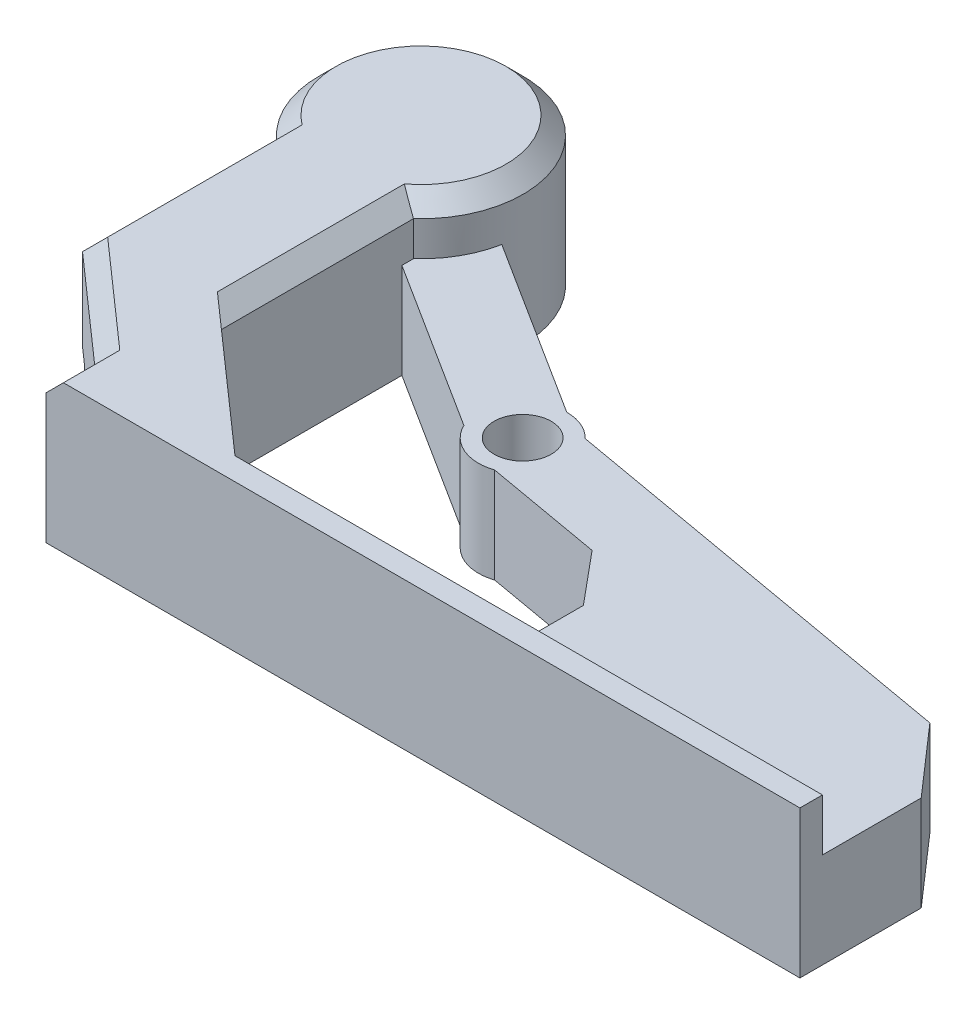
SolidWorks part; units mm, degrees
ref_plane "Front Plane" through (0, 0, 0) normal (0, 0, 1) x (1, 0, 0)
ref_plane "Top Plane" through (0, 0, 0) normal (0, 1, 0) x (1, 0, 0)
ref_plane "Right Plane" through (0, 0, 0) normal (1, 0, 0) x (0, 0, -1)
sketch "Sketch1" plane through (0, 0, 0) normal (0, 1, 0) x (1, 0, 0)
  line L0 (21.75, 0) -> (-21.75, 0)
  line L1 (-21.75, 0) -> (-21.75, 1.3)
  line L2 (-21.75, 1.3) -> (21.75, 1.3)
  line L3 (21.75, 1.3) -> (21.75, 0)
  line L4 (21.75, 0) -> (21.75, 7)
  line L5 (21.75, 7) -> (18.25, 11)
  line L6 (18.25, 11) -> (-7.25, 15.5)
  line L7 (-7.9973, 11.2654) -> (-0.119, 9.8751)
  line L8 (-7.25, 15.5) -> (-7.9973, 11.2654)
  line L9 (-0.119, 9.8751) -> (2.381, 6.8751)
  line L10 (2.381, 6.8751) -> (2.381, 1.3)
  line L11 (-8.9018, 11.6845) -> (-6.5982, 15.3155)
  line L12 (-6.5982, 15.3155) -> (-21.7974, 24.9583)
  line L13 (-21.7974, 24.9583) -> (-24.101, 21.3274)
  line L14 (-24.101, 21.3274) -> (-8.9018, 11.6845)
  line L15 (-7.75, 13.5) -> (-23.8, 23.6826) construction
  line L16 (-21.75, 0) -> (-21.75, 2.8)
  line L17 (-21.75, 2.8) -> (-27.75, 8.1)
  line L18 (-27.75, 8.1) -> (-27.75, 19.3)
  line L19 (-27.75, 19.3) -> (-19.85, 19.3)
  line L20 (-19.85, 19.3) -> (-19.85, 8.1)
  line L21 (-19.85, 8.1) -> (-12.1519, 1.3)
  circle A0 centre (-7.75, 13.5) radius 1.65
  circle A1 centre (-7.75, 13.5) radius 2.55
  circle A2 centre (-23.8, 23.6826) radius 5.9
  point P4 (0, 0)
  dimension "D15" = 3.3
  dimension "D16" = 5.1
  dimension "D25" = 11.8
  dimension "D1" = 1.3
  dimension "D2" = 43.5
  dimension "D3" = 0
  dimension "D4" = 7
  dimension "D5" = 4
  dimension "D6" = 3.5
  dimension "D7" = 29
  dimension "D8" = 15.5
  dimension "D9" = 4.3
  dimension "D10" = 8
  dimension "D11" = 3
  dimension "D12" = 2.5
  dimension "D13" = 29.5
  dimension "D14" = 13.5
  dimension "D17" = 4.3
  dimension "D18" = 18
  dimension "D19" = 2.8
  dimension "D20" = 6
  dimension "D21" = 5.3
  dimension "D22" = 11.2
  dimension "D23" = 7.9
  dimension "D24" = 11.2
extrude "Boss-Extrude1" add sketch "Sketch1" along normal blind 5.5
sketch "Sketch2" plane through (0, 5.5, 0) normal (0, 1, 0) x (1, 0, 0)
  circle A0 centre (-7.75, 13.5) radius 1.65
  dimension "D1" = 3.3
extrude "Cut-Extrude1" cut sketch "Sketch2" against normal blind 5.5
sketch "Sketch3" plane through (0, 5.5, 0) normal (0, 1, 0) x (1, 0, 0)
  line L0 (-19.85, 8.1) -> (-19.85, 19.3)
  line L1 (-27.75, 8.1) -> (-27.75, 19.3)
  line L2 (-27.75, 8.1) -> (-21.75, 2.8)
  line L3 (-21.75, 2.8) -> (-21.75, 0)
  line L4 (-21.75, 0) -> (21.75, 0)
  line L5 (21.75, 0) -> (21.75, 1.3)
  line L6 (21.75, 0) -> (21.75, 7) construction
  line L7 (21.75, 1.3) -> (-12.1519, 1.3)
  line L8 (-12.1519, 1.3) -> (-19.85, 8.1)
  circle A0 centre (-23.8, 23.6826) radius 5.9
  line M8 (2.381, 1.3) -> (-12.1519, 1.3)
  line M9 (-12.1519, 1.3) -> (-19.85, 8.1)
  line M10 (-19.85, 8.1) -> (-19.85, 18.6304)
  arc M14 (-18.0088, 22.5547) -> (-27.75, 19.3) centre (-23.8, 23.6826) ccw
  line M15 (-27.75, 19.3) -> (-27.75, 8.1)
  line M16 (-27.75, 8.1) -> (-21.75, 2.8)
  line M17 (-21.75, 2.8) -> (-21.75, 0)
  line M18 (-21.75, 0) -> (21.75, 0)
  line M19 (21.75, 0) -> (21.75, 7)
  dimension "D1" = 11.8
extrude "Boss-Extrude2" add sketch "Sketch3" along normal blind 3 contours A0 M14 | A0 L7 L0 M15 M16 M17 M18 M19 M8 M9 M10
sketch "Sketch4" plane through (0, 0, 0) normal (0, -1, 0) x (1, 0, 0)
  line L0 (-23.8, -29.5826) -> (-23.8, -7.3)
  line L1 (-23.8, -7.3) -> (-26.8443, -7.3)
  line L2 (-21.75, -2.8) -> (-27.75, -8.1) construction
  line L3 (-26.8443, -7.3) -> (-27.75, -8.1)
  line L4 (-27.75, -8.1) -> (-27.75, -19.3)
  arc A0 (-27.75, -19.3) -> (-18.0088, -22.5547) centre (-23.8, -23.6826) ccw construction
  circle A1 centre (-23.8, -23.6826) radius 5.9
  line M18 (-21.75, -2.8) -> (-27.75, -8.1)
  line M19 (-27.75, -8.1) -> (-27.75, -19.3)
  arc M20 (-27.75, -19.3) -> (-18.0088, -22.5547) centre (-23.8, -23.6826) ccw
  dimension "D2" = 11.8
  dimension "D1" = 0.8
extrude "Cut-Extrude2" cut sketch "Sketch4" against normal offset from surface (2.75 mm away) 5.75 contours L0 A1 M20 | A1 L0 L1 M18 M19
sketch "Sketch5" plane through (0, 0, 0) normal (0, -1, 0) x (1, 0, 0)
  line L0 (21.75, 0) -> (-21.75, 0) construction
  circle A0 centre (-23.8, -23.6826) radius 1.95
  circle A1 centre (-23.8, -13.8826) radius 1.35
  circle A2 centre (-20, -4.3826) radius 1.15
  circle A3 centre (15.0006, -5.5) radius 2
  dimension "D1" = 3.9
  dimension "D3" = 2.7
  dimension "D7" = 2.3
  dimension "D8" = 4
  dimension "D2" = 0
  dimension "D4" = 3.8
  dimension "D5" = 9.5
  dimension "D6" = 9.8
  dimension "D9" = 38.8006
  dimension "D10" = 5.5
extrude "Cut-Extrude3" cut sketch "Sketch5" against normal offset from surface (4.3 mm away) 1.2 up to face at (-1.7017, 5.5, -11.7406)
sketch "Sketch7" plane through (0, 4.3, 0) normal (0, -1, 0) x (1, 0, 0)
  circle A0 centre (-23.8, -13.8826) radius 1.35
  circle A1 centre (-23.8, -23.6826) radius 1.95
  dimension "D1" = 3.9
  dimension "D2" = 2.7
extrude "Cut-Extrude4" cut sketch "Sketch7" against normal offset from surface (3 mm away) 1.2 contours A1 | A0 up to face at (-11.928, 8.5, -7.8314)
chamfer "Chamfer1" distance 1 angle 45 5 edges at (-21.75, 8.5, -1.4) (-24.75, 8.5, -5.45) (-27.75, 8.5, -13.7) (-19.85, 8.5, -13.7) (-23.8, 8.5, -29.5826)
sketch "Sketch8" plane through (0, 0, 0) normal (0, -1, 0) x (1, 0, 0)
  line L0 (-23.8, -7.3) -> (-21.05, -7.3)
  line L1 (-21.05, -7.3) -> (-21.05, -19.8711)
  line L2 (-19.85, -18.6304) -> (-19.85, -8.1) construction
  line L3 (-23.8, -7.3) -> (-23.8, -18.9826)
  circle A0 centre (-23.8, -23.6826) radius 4.7
  arc A1 (-23.8, -29.5826) -> (-18.0088, -22.5547) centre (-23.8, -23.6826) ccw construction
  line M13 (-23.8, -15.2326) -> (-23.8, -21.7326)
  arc M14 (-23.8, -21.7326) -> (-23.8, -25.6326) centre (-23.8, -23.6826) cw
  line M15 (-23.8, -25.6326) -> (-23.8, -29.5826)
  line M26 (-23.8, -7.3) -> (-23.8, -12.5326)
  arc M27 (-23.8, -12.5326) -> (-23.8, -15.2326) centre (-23.8, -13.8826) cw
  dimension "D1" = 1.2
  dimension "D2" = 1.2
extrude "Cut-Extrude5" cut sketch "Sketch8" against normal up to surface (2.75 mm away) contours A0 L1 L0 M26 M27 M13 | A0 M15 M13 M14 up to face at (-25.7752, 2.75, -16.4522)
